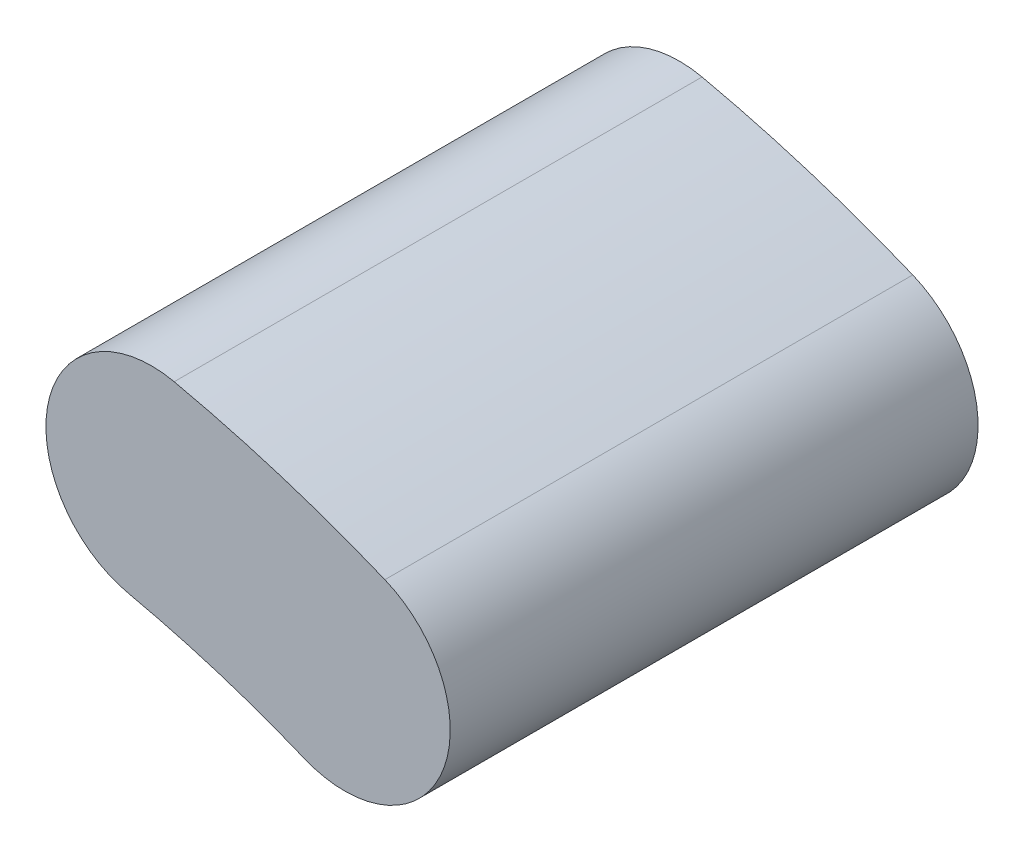
SolidWorks part; units mm, degrees
ref_plane "Front Plane" through (0, 0, 0) normal (0, 0, 1) x (1, 0, 0)
ref_plane "Top Plane" through (0, 0, 0) normal (0, 1, 0) x (1, 0, 0)
ref_plane "Right Plane" through (0, 0, 0) normal (1, 0, 0) x (0, 0, -1)
other "Configuration Table"
sketch "Sketch1" plane through (0, 0, 0) normal (0, 0, 1) x (1, 0, 0)
  arc A0 (83.871, 203.3855) -> (47.2792, 214.8597) centre (0, 0) ccw construction
  arc A1 (91.4956, 221.8751) -> (51.5774, 234.3924) centre (0, 0) ccw
  arc A2 (76.2463, 184.8959) -> (42.9811, 195.327) centre (0, 0) ccw
  arc A3 (76.2463, 184.8959) -> (91.4956, 221.8751) centre (83.871, 203.3855) ccw
  arc A4 (51.5774, 234.3924) -> (42.9811, 195.327) centre (47.2792, 214.8597) ccw
  point P3 (65.8256, 209.9214)
  dimension "D3" = 220
  dimension "D1" = 40
  dimension "D2" = 10
extrude "Boss-Extrude1" add sketch "Sketch1" along normal blind 100
